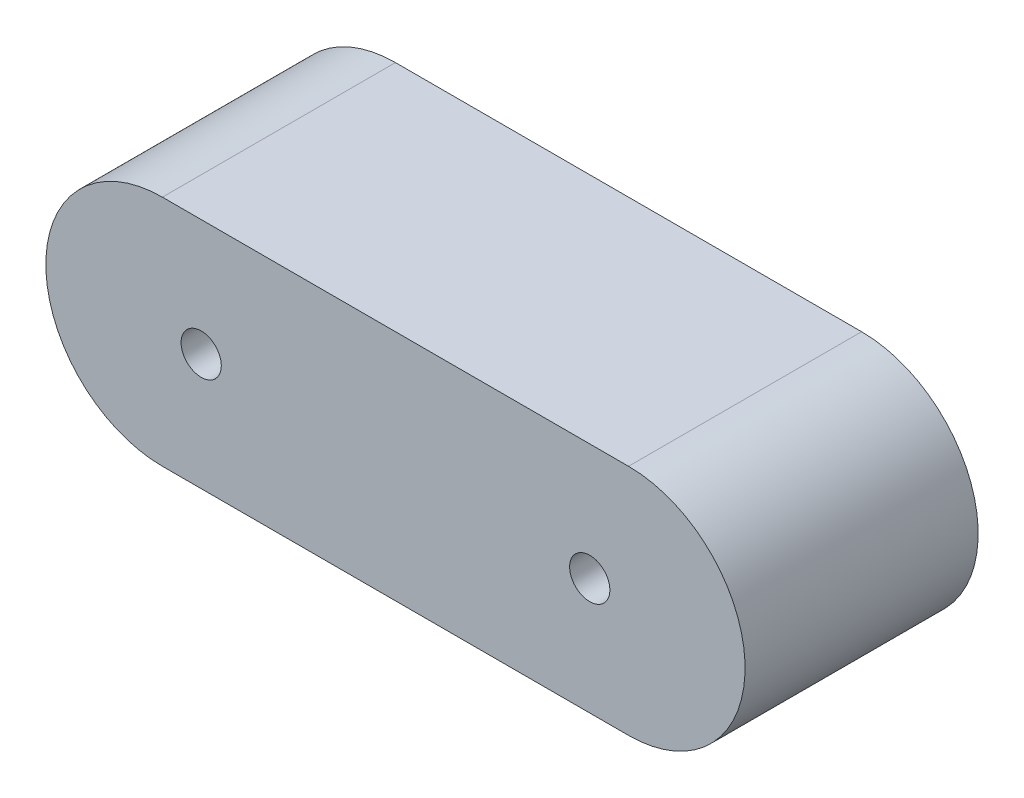
SolidWorks part; units mm, degrees
ref_plane "前视基准面" through (0, 0, 0) normal (0, 0, 1) x (1, 0, 0)
ref_plane "上视基准面" through (0, 0, 0) normal (0, 1, 0) x (1, 0, 0)
ref_plane "右视基准面" through (0, 0, 0) normal (1, 0, 0) x (0, 0, -1)
sketch "草图2" plane through (0, 0, 0) normal (0, 0, 1) x (1, 0, 0)
  line L0 (-20, 0) -> (20, 0) construction
  line L1 (-20, 10) -> (20, 10)
  line L2 (-20, -10) -> (20, -10)
  arc A0 (-20, 10) -> (-20, -10) centre (-20, 0) ccw
  arc A1 (20, -10) -> (20, 10) centre (20, 0) ccw
  point P2 (0, 0)
extrude "凸台-拉伸2" add sketch "草图2" along normal blind 20 contours L2 A1 L1 A0
sketch "草图3" plane through (0, 0, 20) normal (0, 0, 1) x (1, 0, 0)
  circle A0 centre (-16.6705, 0) radius 1.7258
  circle A1 centre (16.6705, 0) radius 1.7258
  dimension "D1" = 2
extrude "切除-拉伸1" cut sketch "草图3" against normal blind 8
